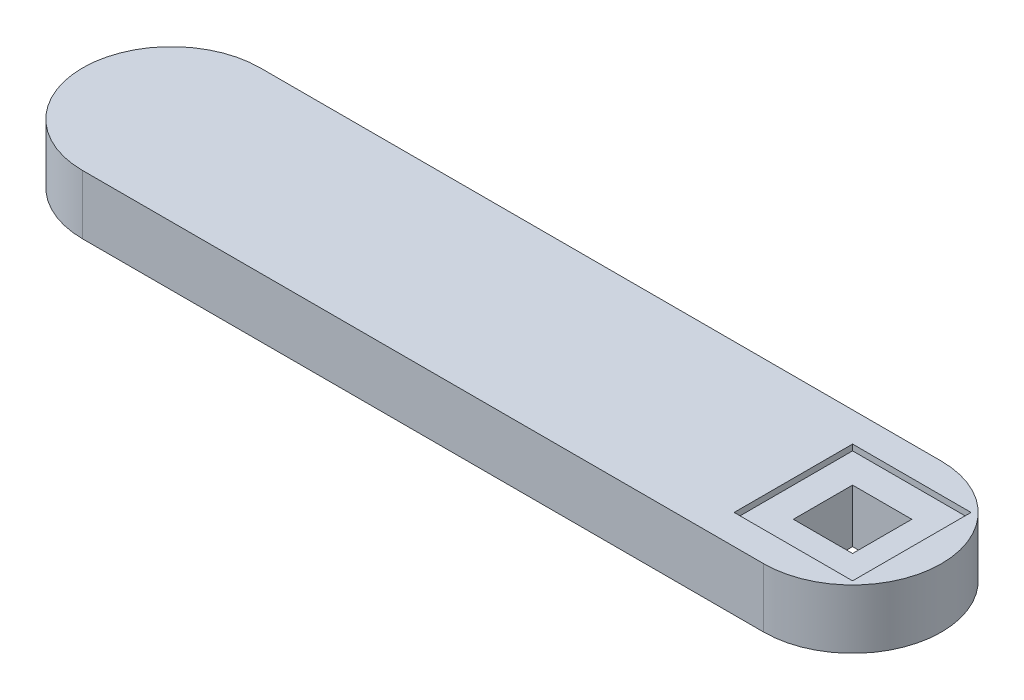
SolidWorks part; units mm, degrees
ref_plane "Front Plane" through (0, 0, 0) normal (0, 0, 1) x (1, 0, 0)
ref_plane "Top Plane" through (0, 0, 0) normal (0, 1, 0) x (1, 0, 0)
ref_plane "Right Plane" through (0, 0, 0) normal (1, 0, 0) x (0, 0, -1)
other "Center of Mass"
sketch "Sketch1" plane through (0, 0, 0) normal (0, 1, 0) x (1, 0, 0)
  line L0 (0, 0) -> (1150, 0) construction
  line L5 (0, 150) -> (1150, 150)
  line L6 (0, -150) -> (1150, -150)
  arc A0 (0, 150) -> (0, -150) centre (0, 0) ccw
  arc A1 (1150, -150) -> (1150, 150) centre (1150, 0) ccw
  point P2 (575, 0)
  dimension "D2" = 150
  dimension "D1" = 1150
extrude "Boss-Extrude1" add sketch "Sketch1" along normal blind 100
sketch "Sketch2" plane through (0, 100, 0) normal (0, 1, 0) x (1, 0, 0)
  line L0 (1150, 150) -> (0, 150) construction
  line L1 (1100, 50) -> (1200, 50)
  line L2 (1100, 50) -> (1100, -50)
  line L3 (1100, -50) -> (1200, -50)
  line L4 (1200, 50) -> (1200, -50)
  line L5 (1100, 50) -> (1200, -50) construction
  line L6 (1100, -50) -> (1200, 50) construction
  arc A1 (1150, -150) -> (1150, 150) centre (1150, 0) ccw construction
  point P0 (1150, 0)
  dimension "D1" = 100
  dimension "D2" = 100
  dimension "D3" = 150
  dimension "D4" = 0
sketch "Sketch3" plane through (0, 0, 0) normal (0, -1, 0) x (1, 0, 0)
  circle A0 centre (0, 0) radius 50
extrude "Boss-Extrude3" add sketch "Sketch3" along normal blind 50
extrude "Cut-Extrude1" cut sketch "Sketch2" against normal blind 100
sketch "Sketch4" plane through (0, 100, 0) normal (0, 1, 0) x (1, 0, 0)
  line L1 (1050, 100) -> (1250, 100)
  line L2 (1050, 100) -> (1050, -100)
  line L3 (1050, -100) -> (1250, -100)
  line L4 (1250, 100) -> (1250, -100)
  line L5 (1050, 100) -> (1250, -100) construction
  line L6 (1050, -100) -> (1250, 100) construction
  point P0 (1150, 0)
  dimension "D1" = 200
  dimension "D2" = 200
extrude "Cut-Extrude2" cut sketch "Sketch4" against normal blind 10
